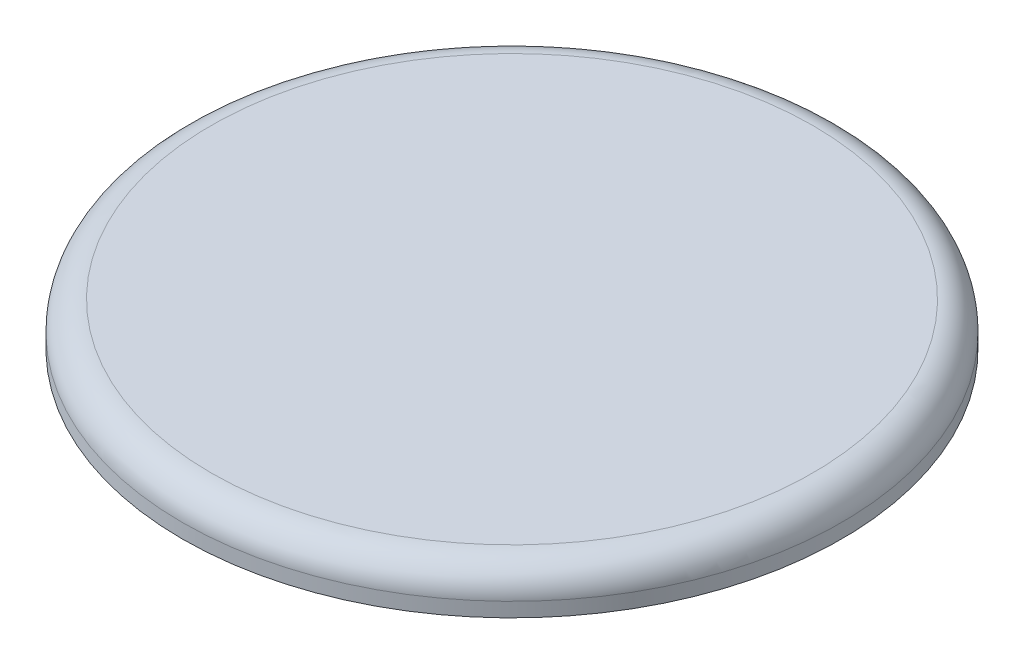
SolidWorks part; units mm, degrees
ref_plane "Plan de face" through (0, 0, 0) normal (0, 0, 1) x (1, 0, 0)
ref_plane "Plan de dessus" through (0, 0, 0) normal (0, 1, 0) x (1, 0, 0)
ref_plane "Plan de droite" through (0, 0, 0) normal (1, 0, 0) x (0, 0, -1)
sketch "Esquisse2" plane through (0, 0, 0) normal (0, 0, 1) x (1, 0, 0)
  line L0 (0, 31.9157) -> (0, -27.4099) construction
  line L1 (0, 5.5) -> (21, 5.5)
  line L2 (23, 3.5) -> (23, 2.5)
  line L3 (23, 2.5) -> (19, 2.5)
  line L4 (19, 2.5) -> (19, 0)
  line L5 (19, 0) -> (17, 0)
  line L6 (17, 0) -> (17, 2.5)
  line L7 (17, 2.5) -> (0, 2.5)
  line L8 (0, 5.5) -> (0, 2.5)
  arc A0 (21, 5.5) -> (23, 3.5) centre (21, 3.5) cw
  point P13 (23, 5.5)
  dimension "D6" = 2
  dimension "D1" = 19
  dimension "D2" = 23
  dimension "D3" = 3
  dimension "D4" = 2.5
  dimension "D5" = 2
revolve "Révolution1" add sketch "Esquisse2" angle 360 about L0
